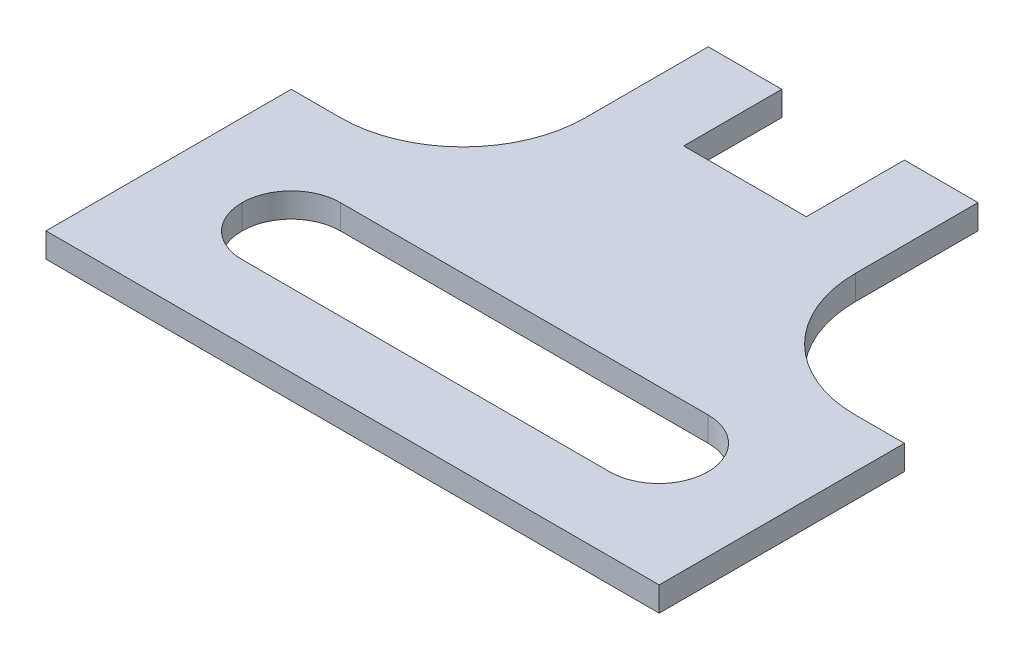
SolidWorks part; units mm, degrees
ref_plane "Front Plane" through (0, 0, 0) normal (0, 0, 1) x (1, 0, 0)
ref_plane "Top Plane" through (0, 0, 0) normal (0, 1, 0) x (1, 0, 0)
ref_plane "Right Plane" through (0, 0, 0) normal (1, 0, 0) x (0, 0, -1)
sketch "Sketch1" plane through (0, 0, 0) normal (0, 1, 0) x (1, 0, 0)
  line L0 (-0.811, 5.6687) -> (-0.811, 10.6687)
  line L1 (-7.811, 0.6687) -> (-5.811, 0.6687)
  line L2 (-7.811, 0.6687) -> (-7.811, -9.3313)
  line L3 (-7.811, -9.3313) -> (17.189, -9.3313)
  line L4 (17.189, 0.6687) -> (17.189, -9.3313)
  line L5 (-0.811, 10.6687) -> (2.189, 10.6687)
  line L6 (2.189, 10.6687) -> (2.189, 6.6687)
  line L7 (2.189, 6.6687) -> (7.189, 6.6687)
  line L8 (7.189, 6.6687) -> (7.189, 10.6687)
  line L9 (7.189, 10.6687) -> (10.189, 10.6687)
  line L10 (10.189, 10.6687) -> (10.189, 5.6687)
  line L11 (15.189, 0.6687) -> (17.189, 0.6687)
  line L13 (-2.811, -2.3313) -> (12.189, -2.3313)
  line L14 (-4.811, -4.3313) -> (-4.811, -4.3469)
  line L15 (-2.811, -6.3469) -> (12.189, -6.3469)
  line L16 (14.189, -4.3313) -> (14.189, -4.3469)
  arc A0 (12.189, -6.3469) -> (14.189, -4.3469) centre (12.189, -4.3469) ccw
  arc A1 (12.189, -2.3313) -> (14.189, -4.3313) centre (12.189, -4.3313) cw
  arc A2 (-4.811, -4.3469) -> (-2.811, -6.3469) centre (-2.811, -4.3469) ccw
  arc A3 (-2.811, -2.3313) -> (-4.811, -4.3313) centre (-2.811, -4.3313) ccw
  arc A4 (10.189, 5.6687) -> (15.189, 0.6687) centre (15.189, 5.6687) ccw
  arc A5 (-0.811, 5.6687) -> (-5.811, 0.6687) centre (-5.811, 5.6687) cw
  point P26 (10.189, 0.6687)
  dimension "D2" = 2
  dimension "D3" = 5
  dimension "D1" = 25
  dimension "D4" = 20
  dimension "D5" = 5
  dimension "D6" = 2
  dimension "D7" = 2
  dimension "D8" = 20
  dimension "D9" = 10
  dimension "D10" = 10
  dimension "D11" = 5
  dimension "D12" = 20
  dimension "D13" = 15
  dimension "D14" = 4
extrude "Boss-Extrude1" add sketch "Sketch1" along normal blind 1
